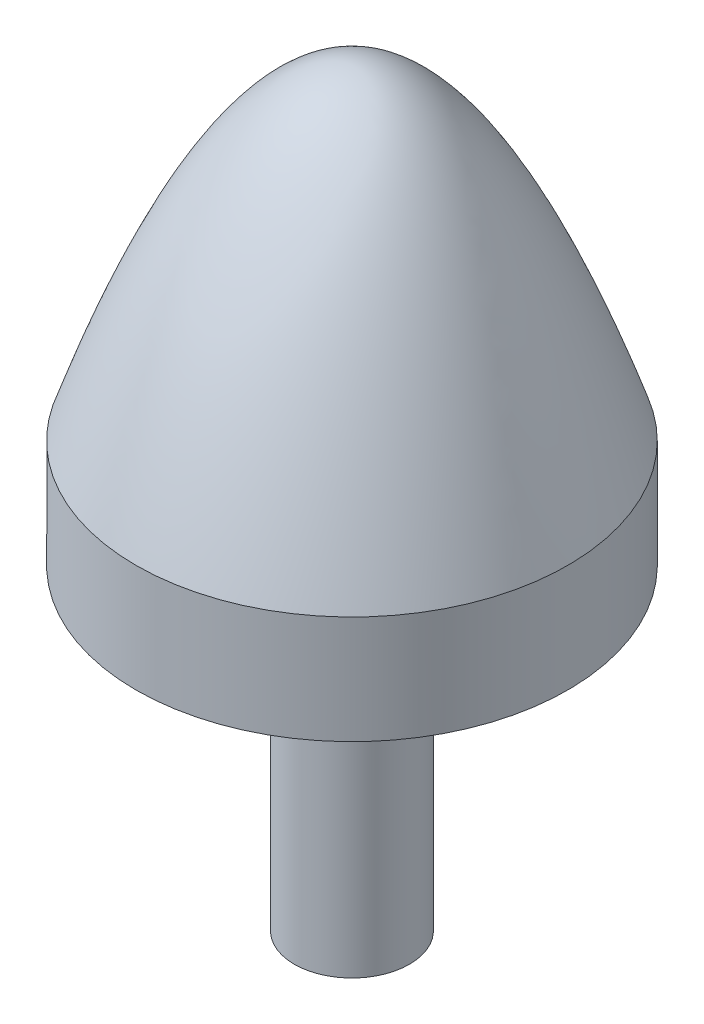
SolidWorks part; units mm, degrees
ref_plane "Front" through (0, 0, 0) normal (0, 0, 1) x (1, 0, 0)
ref_plane "Top" through (0, 0, 0) normal (0, 1, 0) x (1, 0, 0)
ref_plane "Right" through (0, 0, 0) normal (1, 0, 0) x (0, 0, -1)
sketch "Sketch1" plane through (0, 0, 0) normal (0, 0, 1) x (1, 0, 0)
  line L0 (0, 30) -> (0, 0)
  line L1 (0, 0) -> (0, -25)
  line L2 (0, -25) -> (-4, -25)
  line L3 (-4, -25) -> (-4, 0)
  line L4 (-4, 0) -> (-15, 0)
  line L5 (-15, 0) -> (-15, 7.5)
  spline S0 degree 2 poles (-15.8732, 4.804) (-7.1866, 32.381) (1.5, 29.775) knots 0 0 0 1 1 1 construction
  spline S1 degree 2 poles (-15, 7.5) (-7.5, 30) (0, 30) knots 0.050263 0.050263 0.050263 0.91366 0.91366 0.91366
  dimension "D1" = 30
  dimension "D2" = 25
  dimension "D3" = 4
  dimension "D5" = 15
revolve "Revolve1" add sketch "Sketch1" angle 360 about L0
cosmetic thread "Cosmetic Thread1" parameters "D2"=7
sketch "Sketch2" plane through (0, -25, 0) normal (0, -1, 0) x (-1, 0, 0)
  circle A0 centre (0, 0) radius 8.9536
extrude "PostCut" cut sketch "Sketch2" against normal blind 3
